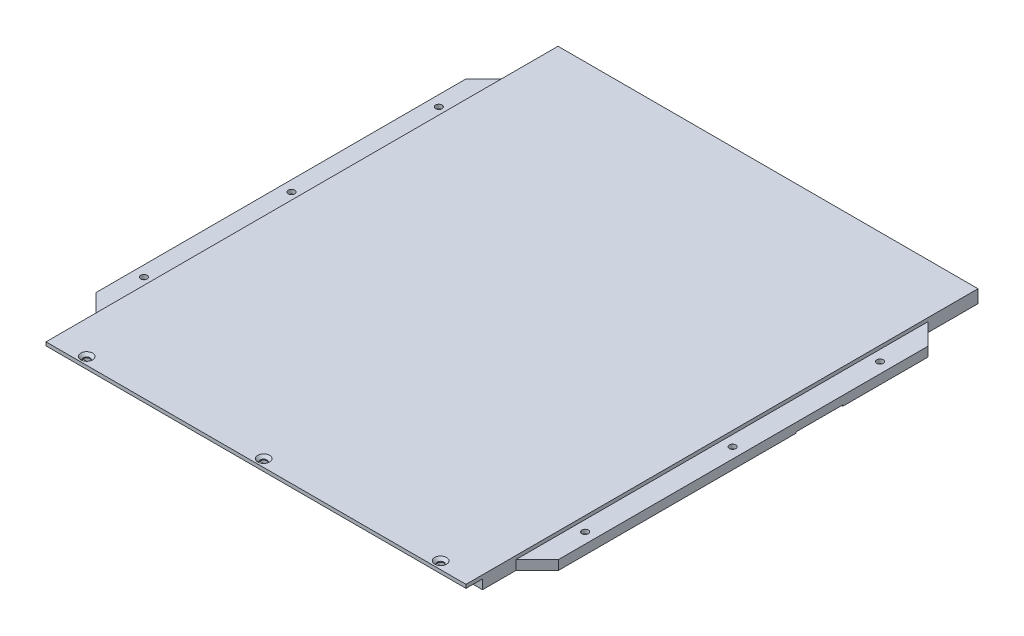
SolidWorks part; units mm, degrees
ref_plane "Front Plane" through (0, 0, 0) normal (0, 0, 1) x (1, 0, 0)
ref_plane "Top Plane" through (0, 0, 0) normal (0, 1, 0) x (1, 0, 0)
ref_plane "Right Plane" through (0, 0, 0) normal (1, 0, 0) x (0, 0, -1)
sketch "Sketch1" plane through (0, 0, 0) normal (0, 1, 0) x (1, 0, 0)
  line L0 (-71.2, 86.8) -> (71.2, 86.8)
  line L1 (-151.3, -88.1) -> (151.3, -88.1) construction
  line L2 (-151.3, -88.1) -> (-151.3, 88.1) construction
  line L3 (-151.3, 88.1) -> (151.3, 88.1) construction
  line L4 (151.3, -88.1) -> (151.3, 88.1) construction
  line L5 (-151.3, -88.1) -> (151.3, 88.1) construction
  line L6 (-151.3, 88.1) -> (151.3, -88.1) construction
  line L7 (-71.2, 86.8) -> (-71.2, -86.8)
  line L8 (71.2, 86.8) -> (71.2, -86.8)
  line L9 (-71.2, -86.8) -> (71.2, -86.8)
  point P0 (0, 0)
  dimension "D1" = 302.6
  dimension "D2" = 176.2
  dimension "D3" = 80.1
  dimension "D4" = 80.1
  dimension "D5" = 1.3
  dimension "D6" = 1.3
extrude "Boss-Extrude1" add sketch "Sketch1" against normal blind 4.4
sketch "Sketch2" plane through (0, -4.4, 0) normal (0, -1, 0) x (1, 0, 0)
  line L0 (71.2, 86.8) -> (-71.2, 86.8)
  line L1 (71.2, 86.8) -> (71.2, 81.2)
  line L2 (-71.2, 86.8) -> (-71.2, 81.2)
  line L3 (71.2, 81.2) -> (-71.2, 81.2)
  line L4 (-71.2, 86.8) -> (71.2, 86.8) construction
  dimension "D1" = 5.6
extrude "Cut-Extrude1" cut sketch "Sketch2" against normal offset from surface (3.2 mm away) 1.2 up to face at (0, 0, 0)
sketch "Sketch3" plane through (0, 0, 0) normal (0, 1, 0) x (1, 0, 0)
  line L0 (0, -84.2) -> (-60, -84.2) construction
  line L1 (0, -84.2) -> (60, -84.2) construction
  line L2 (-71.2, -86.8) -> (71.2, -86.8) construction
  line L3 (0, -84.2) -> (0, -81.2) construction
  line L4 (-71.2, -81.2) -> (71.2, -81.2) construction
  circle A0 centre (60, -84.2) radius 1.1
  circle A1 centre (-60, -84.2) radius 1.1
  circle A2 centre (0, -84.2) radius 1.1
  dimension "D1" = 2.2
  dimension "D2" = 60
  dimension "D3" = 3
extrude "Cut-Extrude2" cut sketch "Sketch3" against normal up to next
sketch "Sketch4" plane through (0, 0, -86.8) normal (0, 0, -1) x (-1, 0, 0)
  line L0 (60, -2.2) -> (0, -2.2) construction
  line L1 (0, -2.2) -> (-60, -2.2) construction
  line L2 (-71.2, 0) -> (71.2, 0) construction
  line L3 (0, 0) -> (0, -4.4) construction
  line L4 (-71.2, -4.4) -> (71.2, -4.4) construction
  line L5 (71.2, 0) -> (-71.2, 0) construction
  circle A0 centre (0, -2.2) radius 0.9
  circle A1 centre (60, -2.2) radius 0.9
  circle A2 centre (-60, -2.2) radius 0.9
  dimension "D2" = 1.8
  dimension "D1" = 60
extrude "Cut-Extrude3" cut sketch "Sketch4" against normal blind 9
chamfer "Chamfer2" distance 0.9 angle 45 3 edges at (0, 0, 85.3) (60, 0, 85.3) (-60, 0, 85.3)
sketch "Sketch5" plane through (0, -4.4, 0) normal (0, -1, 0) x (1, 0, 0)
  line L0 (-71.2, 69.8586) -> (-78.4, 62.6586)
  line L1 (-71.2, -86.8) -> (-71.2, 86.8) construction
  line L2 (-78.4, 62.6586) -> (-78.4, -62.6586)
  line L3 (-78.4, -62.6586) -> (-71.2, -69.8586)
  line L4 (-71.2, -69.8586) -> (-71.2, 69.8586)
  line L5 (71.2, 69.8586) -> (78.4, 62.6586)
  line L6 (71.2, -86.8) -> (71.2, 86.8) construction
  line L7 (78.4, 62.6586) -> (78.4, -62.6586)
  line L8 (78.4, -62.6586) -> (71.2, -69.8586)
  line L9 (71.2, -69.8586) -> (71.2, 69.8586)
  line L10 (-78.4, 62.8) -> (-71.2, 70) construction
  line L11 (-71.2, 70) -> (-71.2, -70) construction
  line L12 (-71.2, -70) -> (-78.4, -62.8) construction
  line L13 (0, 0) -> (-71.2, 0) construction
  line L14 (-151.3, -88.1) -> (151.3, 88.1) construction
  line L15 (0, 0) -> (71.2, 0) construction
  dimension "D1" = 45
  dimension "D2" = 45
  dimension "D3" = 45
  dimension "D4" = 45
  dimension "D5" = 140
  dimension "D6" = 0.1
  dimension "D7" = 0.1
  dimension "D8" = 7.2
extrude "Boss-Extrude2" add sketch "Sketch5" against normal up to surface (3.2 mm away) up to face at (60, -1.2, 85.3)
sketch "Sketch6" plane through (0, -4.4, 0) normal (0, -1, 0) x (1, 0, 0)
  line L0 (71.2, -86.8) -> (71.2, 86.8) construction
  line L1 (74.8, 0) -> (74.8, -50) construction
  line L2 (74.8, 50) -> (74.8, 0) construction
  line L3 (78.4, 0) -> (74.8, 0) construction
  line L4 (78.4, -62.6586) -> (78.4, 62.6586) construction
  line L5 (-74.8, 50) -> (-74.8, 0) construction
  line L6 (-74.8, 0) -> (-74.8, -50) construction
  line L7 (-78.4, 0) -> (-74.8, 0) construction
  line L8 (-78.4, 62.6586) -> (-78.4, -62.6586) construction
  line L9 (-71.2, -86.8) -> (-71.2, 86.8) construction
  circle A0 centre (74.8, 50) radius 1.1
  circle A1 centre (74.8, 0) radius 1.1
  circle A2 centre (74.8, -50) radius 1.1
  circle A3 centre (-74.8, 50) radius 1.1
  circle A4 centre (-74.8, 0) radius 1.1
  circle A5 centre (-74.8, -50) radius 1.1
  dimension "D2" = 2.2
  dimension "D1" = 3.6
  dimension "D3" = 50
  dimension "D4" = 3.6
extrude "Cut-Extrude4" cut sketch "Sketch6" against normal through all
sketch "Sketch7" plane through (0, -4.4, 0) normal (0, -1, 0) x (1, 0, 0)
  line L0 (-78.4, 62.6586) -> (-78.4, -62.6586) construction
  line L1 (72.4, 48.6144) -> (74.8, 47.2287)
  line L2 (74.8, 47.2287) -> (77.2, 48.6144)
  line L3 (77.2, 48.6144) -> (77.2, 51.3856)
  line L4 (77.2, 51.3856) -> (74.8, 52.7713)
  line L5 (74.8, 52.7713) -> (72.4, 51.3856)
  line L6 (72.4, 51.3856) -> (72.4, 48.6144)
  line L7 (77.2, 1.3856) -> (74.8, 2.7713)
  line L8 (74.8, 2.7713) -> (72.4, 1.3856)
  line L9 (72.4, 1.3856) -> (72.4, -1.3856)
  line L10 (72.4, -1.3856) -> (74.8, -2.7713)
  line L11 (74.8, -2.7713) -> (77.2, -1.3856)
  line L12 (77.2, -1.3856) -> (77.2, 1.3856)
  line L13 (77.2, -48.6144) -> (74.8, -47.2287)
  line L14 (74.8, -47.2287) -> (72.4, -48.6144)
  line L15 (72.4, -48.6144) -> (72.4, -51.3856)
  line L16 (72.4, -51.3856) -> (74.8, -52.7713)
  line L17 (74.8, -52.7713) -> (77.2, -51.3856)
  line L18 (77.2, -51.3856) -> (77.2, -48.6144)
  line L19 (-72.4, -51.3856) -> (-72.4, -48.6144)
  line L20 (-72.4, -48.6144) -> (-74.8, -47.2287)
  line L21 (-74.8, -47.2287) -> (-77.2, -48.6144)
  line L22 (-77.2, -48.6144) -> (-77.2, -51.3856)
  line L23 (-77.2, -51.3856) -> (-74.8, -52.7713)
  line L24 (-74.8, -52.7713) -> (-72.4, -51.3856)
  line L25 (-72.4, -1.3856) -> (-72.4, 1.3856)
  line L26 (-72.4, 1.3856) -> (-74.8, 2.7713)
  line L27 (-74.8, 2.7713) -> (-77.2, 1.3856)
  line L28 (-77.2, 1.3856) -> (-77.2, -1.3856)
  line L29 (-77.2, -1.3856) -> (-74.8, -2.7713)
  line L30 (-74.8, -2.7713) -> (-72.4, -1.3856)
  line L31 (-72.4, 48.6144) -> (-72.4, 51.3856)
  line L32 (-72.4, 51.3856) -> (-74.8, 52.7713)
  line L33 (-74.8, 52.7713) -> (-77.2, 51.3856)
  line L34 (-77.2, 51.3856) -> (-77.2, 48.6144)
  line L35 (-77.2, 48.6144) -> (-74.8, 47.2287)
  line L36 (-74.8, 47.2287) -> (-72.4, 48.6144)
  circle A0 centre (74.8, 50) radius 2.4 construction
  circle A1 centre (74.8, 0) radius 2.4 construction
  circle A2 centre (74.8, -50) radius 2.4 construction
  circle A3 centre (-74.8, -50) radius 2.4 construction
  circle A4 centre (-74.8, 0) radius 2.4 construction
  circle A5 centre (-74.8, 50) radius 2.4 construction
  dimension "D1" = 4.8
extrude "Cut-Extrude5" cut sketch "Sketch7" against normal blind 1.8
sketch "Sketch8" plane through (0, -4.4, 0) normal (0, -1, 0) x (1, 0, 0)
  line L0 (78.4, -17.9) -> (-29.05, -17.9)
  line L1 (78.4, -62.6586) -> (78.4, 62.6586) construction
  line L3 (-29.05, -33.8) -> (-29.05, -86.8)
  line L4 (71.2, -86.8) -> (-71.2, -86.8) construction
  line L5 (-29.05, -86.8) -> (-44.95, -86.8)
  line L8 (-29.05, -33.8) -> (78.4, -33.8)
  line L9 (78.4, -17.9) -> (78.4, -33.8)
  line L11 (-151.3, 88.1) -> (151.3, 88.1) construction
  line L12 (-29.05, -17.9) -> (-44.95, -33.8)
  line L13 (-44.95, -33.8) -> (-44.95, -86.8)
  line L14 (-151.3, 88.1) -> (-151.3, -88.1) construction
  point P4 (-37, -86.8)
  point P14 (78.4, -25.85)
  dimension "D1" = 113.95
  dimension "D2" = 15.9
  dimension "D3" = 114.3
extrude "Cut-Extrude6" cut sketch "Sketch8" against normal blind 0.4
equation "\"LCD_Height\"= 158mm"
equation "\"LCD_Width\"= 268mm"
equation "\"LCD_PCB_Height\"= 10mm"
equation "\"LCD_PCB_Width\"= 189"
equation "\"LCD_PCB_LOff\"= 38.5"
equation "\"LCD_Thick\"= 2.9mm"
equation "\"LCD_TBezel\"= 4.6mm"
equation "\"LCD_LBezel\"= 4.94mm"
equation "\"LCD_RBezel\"= 6.94mm"
equation "\"LCD_BBezel\"= 9.4mm"
equation "\"Wing_Height\"= 11.5mm"
equation "\"Wing_Width\"= 5mm"
equation "\"Wing_Corner\"= 1mm"
equation "\"Wing_Hole_VOff\"= 3.5mm"
equation "\"Wing_Hole_HOff\"= 2.8mm"
equation "\"Wing_Spacing\"= 128.9 + 2 * \"Wing_Hole_VOff\" - \"Wing_Height\""
equation "\"Wing_TOff\"= 8.35 - \"Wing_Hole_VOff\""
equation "\"Wing_DOff\"= 0.7mm"
equation "\"Wing_Thick\"= 0.3mm"
equation "\"Print_Gap\"= 0.2mm"
equation "\"Pin1_Pos\"= 89.75mm"
equation "\"Pin_Space\"= 0.5mm"
equation "\"Pin_num\"= 30"
equation "\"Min_Thick\"= 1.2mm"
equation "\"Nut_Width\"= 4.8mm"
equation "\"Nut_Height\"= 5.6mm"
equation "\"Nut_Thick\"= 1.6mm"
equation "\"Screw_Hole\"= 2.2mm"
equation "\"Screw_Chamf\"= 0.9mm"
equation "\"Bezel_Gap\"= 0.4mm"
equation "\"USB_Width\"= 16mm"
equation "\"Corner_Radius\"= 6mm"
equation "\"Stand_Tilt\"= 8"
equation "\"Screen_Tilt\"= 24"
equation "\"Stand_Splay\"= 16"
equation "\"D1@Sketch1\"=\"LCD_Width\" + \"Print_Gap\" + \"Min_Thick\" * 2 + \"USB_Width\" * 2"
equation "\"D2@Sketch1\"= \"LCD_Height\" + \"LCD_PCB_Height\" + \"Print_Gap\" + \"Nut_Height\" + \"Min_Thick\" * 2"
equation "\"D4@Sketch1\"=80 + \"Print_Gap\" / 2"
equation "\"D3@Sketch1\"= 80 + \"Print_Gap\" / 2"
equation "\"D5@Sketch1\"=\"Min_Thick\" + \"Print_Gap\" / 2"
equation "\"D6@Sketch1\"=\"Print_Gap\" / 2 + \"Min_Thick\""
equation "\"D1@Boss-Extrude1\"=8 - 0.6 - \"Print_Gap\" / 2 -\"LCD_Thick\""
equation "\"D1@Sketch2\"=\"Nut_Height\""
equation "\"D1@Cut-Extrude1\"=\"Min_Thick\""
equation "\"D1@Sketch3\"=\"Screw_Hole\""
equation "\"D3@Sketch3\"=\"Print_Gap\" + \"Nut_Height\" / 2"
equation "\"D2@Sketch4\"=\"Screw_Hole\" - 2 * \"Print_Gap\" "
equation "\"D1@Chamfer2\"=\"Screw_Chamf\""
equation "\"D6@Sketch5\"=\"Print_Gap\" / 2"
equation "\"D8@Sketch5\"=\"Nut_Width\" + 2 * \"Min_Thick\""
equation "\"D1@Sketch6\"=\"Nut_Width\" / 2 + \"Min_Thick\""
equation "\"D2@Sketch6\"=\"Screw_Hole\""
equation "\"D4@Sketch6\"=\"Nut_Width\" / 2 + \"Min_Thick\" "
equation "\"D1@Sketch7\"=\"Nut_Width\""
equation "\"D1@Cut-Extrude5\"=\"Nut_Thick\" + \"Print_Gap\""
equation "\"D1@Sketch8\"=\"Min_Thick\" + \"Nut_Height\" + \"Print_Gap\"/2 + \"Wing_TOff\" + \"Wing_Height\" - \"Wing_Hole_VOff\" + \"Wing_Spacing\" - (\"Nut_Width\" + 2 * \"Min_Thick\" + 22) / 2 - (118 - 102.6 + \"Print_Gap\")"
equation "\"D2@Sketch8\"=31 * 0.5 + 2 * \"Print_Gap\""
equation "\"D1@Cut-Extrude6\"=\"Print_Gap\" * 2"
equation "\"D3@Sketch8\"=0.5 * (29) / 2 + 89.75 + \"Min_Thick\" + \"USB_Width\" + \"Print_Gap\" / 2"
